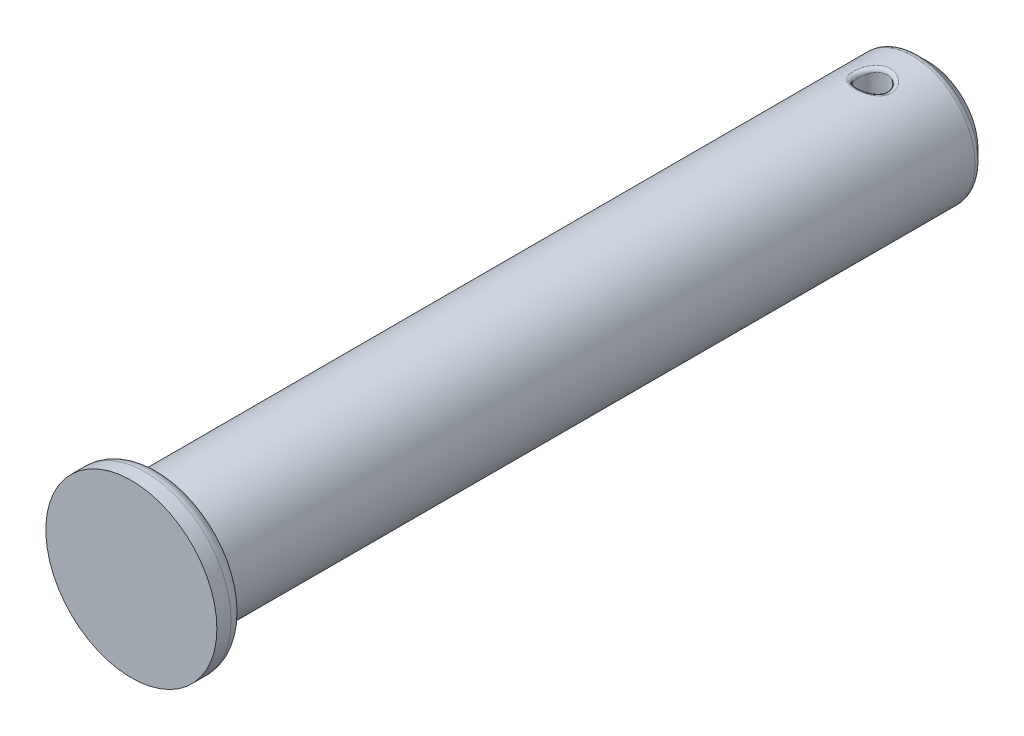
SolidWorks part; units mm, degrees
ref_plane "Front Plane" through (0, 0, 0) normal (0, 0, 1) x (1, 0, 0)
ref_plane "Top Plane" through (0, 0, 0) normal (0, 1, 0) x (1, 0, 0)
ref_plane "Right Plane" through (0, 0, 0) normal (1, 0, 0) x (0, 0, -1)
sketch "Sketch1" plane through (0, 0, 0) normal (0, 0, 1) x (1, 0, 0)
  circle A0 centre (0, 0) radius 3.4925
  dimension "D1" = 6.985
extrude "Boss-Extrude1" add sketch "Sketch1" along normal blind 42.8625
sketch "Sketch2" plane through (0, 0, 42.8625) normal (0, 0, 1) x (1, 0, 0)
  circle A2 centre (0, 0) radius 4.7625
  circle A3 centre (0, 0) radius 4.7625
  dimension "D1" = 1.27
extrude "Boss-Extrude2" add sketch "Sketch2" along normal blind 1.5875
sketch "Sketch3" plane through (0, 0, 0) normal (0, 1, 0) x (1, 0, 0)
  circle A0 centre (0, -3.175) radius 0.7938
  dimension "D1" = 1.5875
  dimension "D2" = 3.175
extrude "Cut-Extrude1" cut sketch "Sketch3" against normal through all both and the other way through all
fillet "Fillet1" radius 0.1984 2 edges at (-0.1599, -3.4888, 2.3975) (0.1599, 3.4888, 2.3975)
fillet "Fillet3" radius 0.7937 1 edges at (4.7625, 0, 42.8625)
chamfer "Chamfer1" distance 0.7937 angle 45 1 edges at (3.4925, 0, 0)
fillet "Fillet4" radius 0.3969 2 edges at (2.6987, 0, 0) (3.4925, 0, 0.7938)
